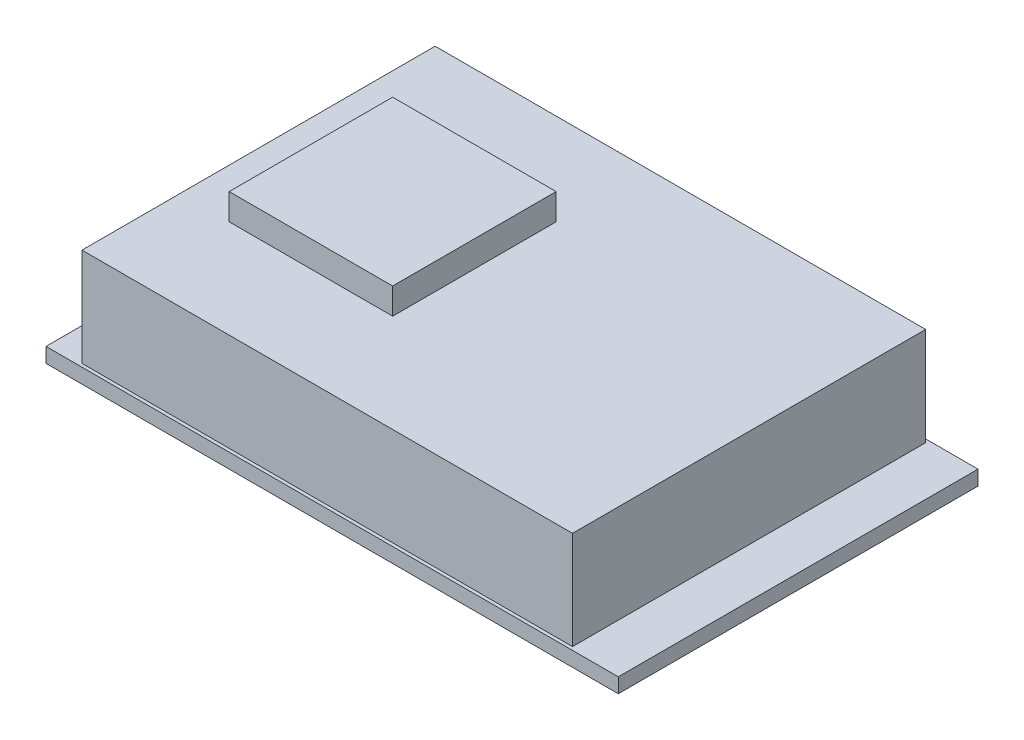
SolidWorks part; units mm, degrees
ref_plane "Front Plane" through (0, 0, 0) normal (0, 0, 1) x (1, 0, 0)
ref_plane "Top Plane" through (0, 0, 0) normal (0, 1, 0) x (1, 0, 0)
ref_plane "Right Plane" through (0, 0, 0) normal (1, 0, 0) x (0, 0, -1)
sketch "Sketch1" plane through (0, 0, 0) normal (0, 1, 0) x (1, 0, 0)
  line L1 (-87.5, 55) -> (87.5, 55)
  line L2 (-87.5, 55) -> (-87.5, -55)
  line L3 (-87.5, -55) -> (87.5, -55)
  line L4 (87.5, 55) -> (87.5, -55)
  line L5 (-87.5, 55) -> (87.5, -55) construction
  line L6 (-87.5, -55) -> (87.5, 55) construction
  point P0 (0, 0)
  dimension "D1" = 110
  dimension "D2" = 175
extrude "Boss-Extrude1" add sketch "Sketch1" along normal blind 4.5
sketch "Sketch2" plane through (0, 4.5, 0) normal (0, 1, 0) x (1, 0, 0)
  line L0 (87.5, -55) -> (87.5, 55) construction
  line L1 (72.5, 54) -> (-77.5, 54)
  line L2 (72.5, 54) -> (72.5, -54)
  line L3 (72.5, -54) -> (-77.5, -54)
  line L4 (-77.5, 54) -> (-77.5, -54)
  line L5 (-87.5, 55) -> (-87.5, -55) construction
  line L8 (87.5, 55) -> (-87.5, 55) construction
  line L9 (-87.5, -55) -> (87.5, -55) construction
  dimension "D1" = 15
  dimension "D2" = 10
  dimension "D3" = 1
  dimension "D4" = 1
extrude "Boss-Extrude2" add sketch "Sketch2" along normal blind 30
sketch "Sketch3" plane through (0, 34.5, 0) normal (0, 1, 0) x (1, 0, 0)
  line L0 (72.5, 54) -> (-77.5, 54) construction
  line L1 (-62.5, 26) -> (-12.5, 26)
  line L2 (-62.5, 26) -> (-62.5, -24)
  line L3 (-62.5, -24) -> (-12.5, -24)
  line L4 (-12.5, 26) -> (-12.5, -24)
  line L5 (-77.5, -54) -> (72.5, -54) construction
  line L6 (-77.5, 54) -> (-77.5, -54) construction
  dimension "D1" = 15
  dimension "D2" = 50
  dimension "D3" = 50
  dimension "D4" = 30
  dimension "D5" = 28
extrude "Boss-Extrude3" add sketch "Sketch3" along normal blind 8 contours L1 L4 L3 L2
